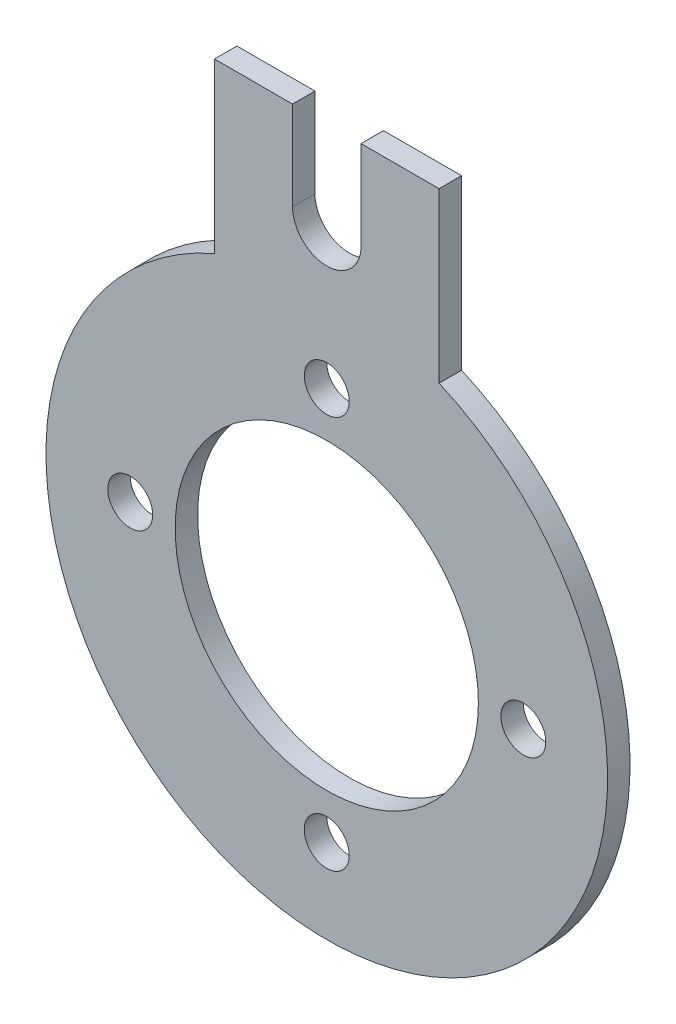
SolidWorks part; units mm, degrees
ref_plane "前视基准面" through (0, 0, 0) normal (0, 0, 1) x (1, 0, 0)
ref_plane "上视基准面" through (0, 0, 0) normal (0, 1, 0) x (1, 0, 0)
ref_plane "右视基准面" through (0, 0, 0) normal (1, 0, 0) x (0, 0, -1)
sketch "草图1" plane through (0, 0, 0) normal (0, 0, 1) x (1, 0, 0)
  circle A0 centre (0, 0) radius 25
  circle A1 centre (0, 17.5) radius 2
  circle A2 centre (17.5, 0) radius 2
  circle A3 centre (0, -17.5) radius 2
  circle A4 centre (-17.5, 0) radius 2
  point P14 (0, 0)
  dimension "D1" = 50
  dimension "D2" = 4
  dimension "D3" = 17.5
  dimension "D4" = 4
extrude "凸台-拉伸1" add sketch "草图1" along normal blind 2
sketch "草图2" plane through (0, 0, 2) normal (0, 0, 1) x (1, 0, 0)
  line L0 (-10, 22.9129) -> (-10, 37.9129)
  line L1 (10, 22.9129) -> (10, 37.9129)
  line L2 (-3.05, 30) -> (-3.05, 37.9129)
  line L3 (3.05, 30) -> (3.05, 37.9129)
  line L4 (3.05, 37.9129) -> (10, 37.9129)
  line L5 (-10, 37.9129) -> (-3.05, 37.9129)
  arc A0 (-3.05, 30) -> (3.05, 30) centre (0, 30) ccw
  circle A1 centre (0, 0) radius 25 construction
  arc A2 (10, 22.9129) -> (-10, 22.9129) centre (0, 0) ccw
  dimension "D1" = 6.1
  dimension "D2" = 30
  dimension "D3" = 10
  dimension "D4" = 10
  dimension "D5" = 15
  dimension "D6" = 15
extrude "凸台-拉伸2" add sketch "草图2" against normal blind 2
sketch "草图3" plane through (0, 0, 2) normal (0, 0, 1) x (1, 0, 0)
  circle A0 centre (0, 0) radius 13.5
  dimension "D1" = 27
extrude "切除-拉伸1" cut sketch "草图3" against normal blind 2
